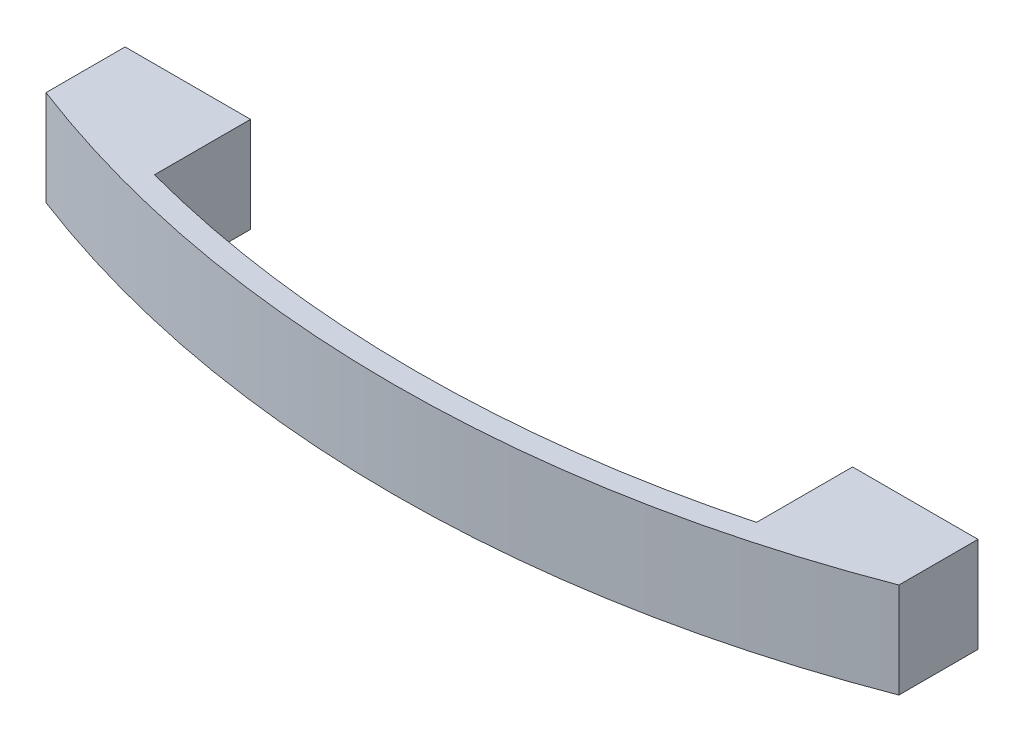
SolidWorks part; units mm, degrees
ref_plane "前视基准面" through (0, 0, 0) normal (0, 0, 1) x (1, 0, 0)
ref_plane "上视基准面" through (0, 0, 0) normal (0, 1, 0) x (1, 0, 0)
ref_plane "右视基准面" through (0, 0, 0) normal (1, 0, 0) x (0, 0, -1)
sketch "草图1" plane through (0, 0, 0) normal (0, 1, 0) x (1, 0, 0)
  line L0 (60, -225.1422) -> (60, -205)
  line L1 (60, -205) -> (85, -205)
  line L2 (85, -205) -> (85, -221.7685)
  line L3 (0, 0) -> (0, -50000) construction
  line L4 (-60, -225.1422) -> (-60, -205)
  line L5 (-60, -205) -> (-85, -205)
  line L6 (-85, -205) -> (-85, -221.7685)
  arc A0 (-60, -225.1422) -> (60, -225.1422) centre (0, 0) ccw
  arc A1 (-85, -221.7685) -> (85, -221.7685) centre (0, 0) ccw
  dimension "D1" = 466
  dimension "D2" = 475
  dimension "D3" = 25
  dimension "D4" = 60
  dimension "D5" = 205
extrude "凸台-拉伸1" add sketch "草图1" along normal blind 19
chamfer "倒角1" distance 1 angle 45 8 edges at (-60, 9.5, 205) (-72.5, 19, 205) (-85, 9.5, 205) (-72.5, 0, 205) (85, 9.5, 205) (72.5, 19, 205) (60, 9.5, 205) (72.5, 0, 205)
